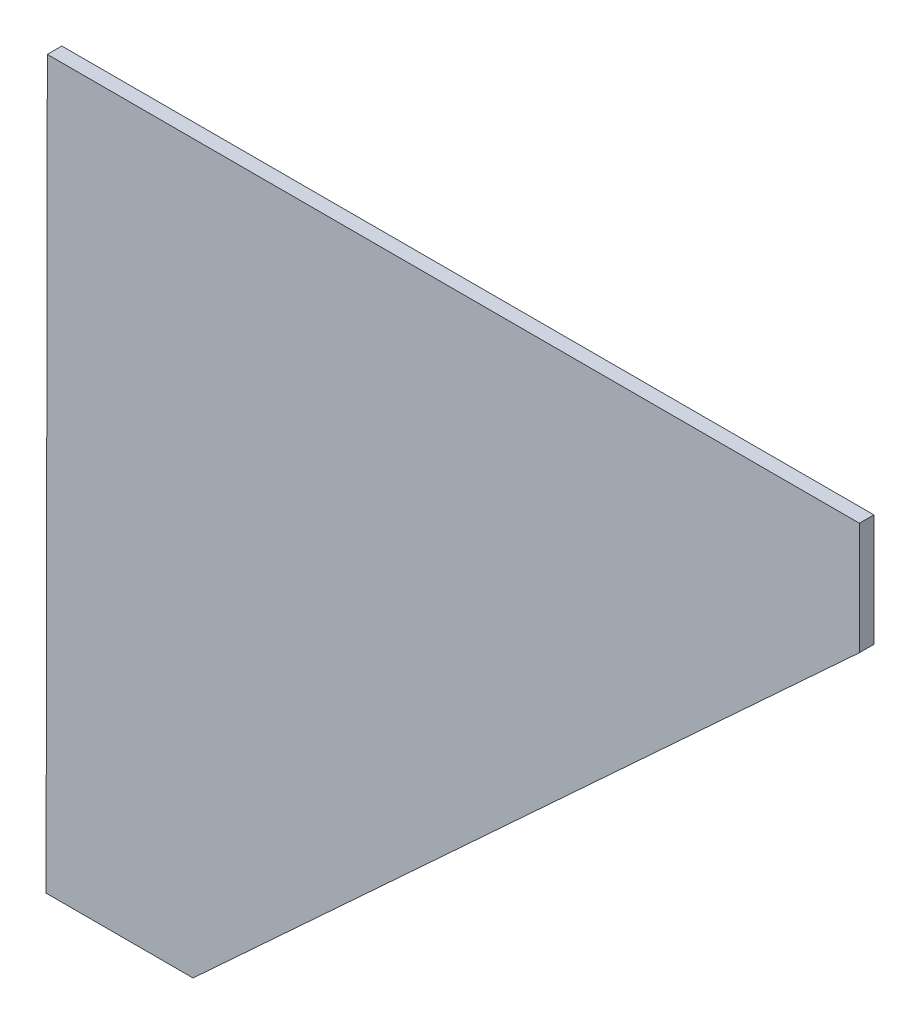
SolidWorks part; units mm, degrees
material "ASTM A500 Grade B"
ref_plane "Front Plane" through (0, 0, 0) normal (0, 0, 1) x (1, 0, 0)
ref_plane "Top Plane" through (0, 0, 0) normal (0, 1, 0) x (1, 0, 0)
ref_plane "Right Plane" through (0, 0, 0) normal (1, 0, 0) x (0, 0, -1)
sketch "Sketch1" plane through (0, 0, 0) normal (0, 0, 1) x (1, 0, 0)
  line L0 (-1993.5728, -463.2297) -> (-1555.878, -59.3697)
  line L1 (-1555.878, -59.3697) -> (-1555.878, 14.2903)
  line L2 (-1555.878, 14.2903) -> (-2089.278, 14.2903)
  line L3 (-2089.278, 14.2903) -> (-2090.0928, -463.2297)
  line L5 (-2090.0928, -463.2297) -> (-1993.5728, -463.2297)
  dimension "D1" = 96.52
  dimension "D2" = 73.66
  dimension "D3" = 533.4
  dimension "D4" = 477.52
extrude "Boss-Extrude1" add sketch "Sketch1" along normal blind 9.525
fillet "Fillet1" [suppressed] radius 1.5875
